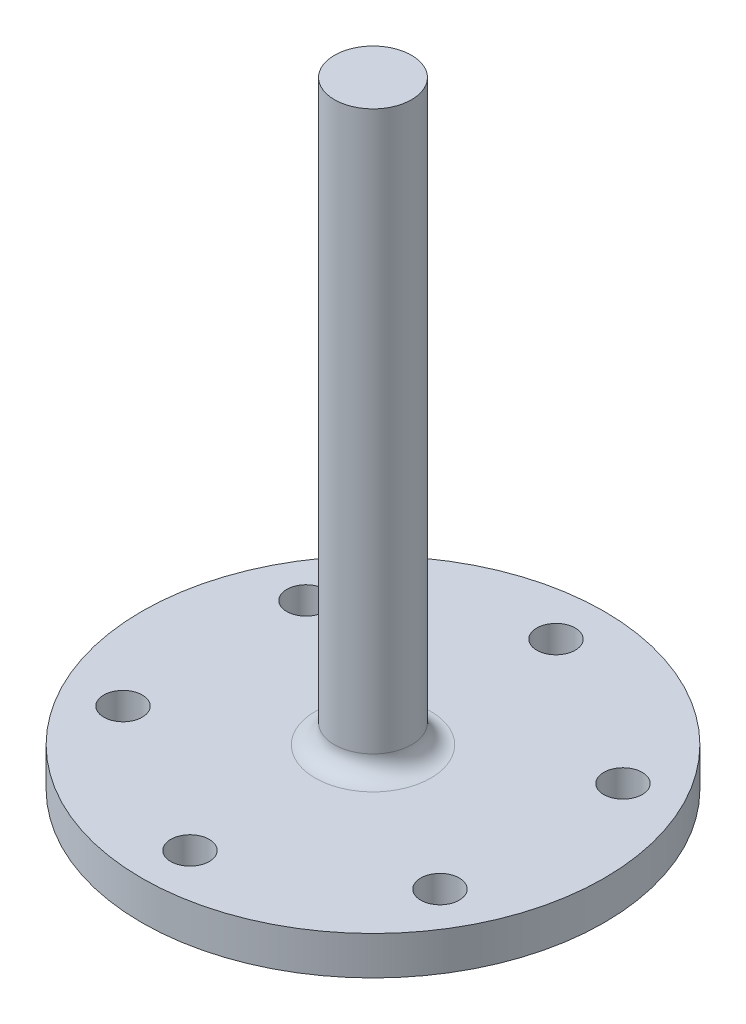
SolidWorks part; units mm, degrees
ref_plane "Front Plane" through (0, 0, 0) normal (0, 0, 1) x (1, 0, 0)
ref_plane "Top Plane" through (0, 0, 0) normal (0, 1, 0) x (1, 0, 0)
ref_plane "Right Plane" through (0, 0, 0) normal (1, 0, 0) x (0, 0, -1)
sketch "Sketch1" plane through (0, 0, 0) normal (0, 1, 0) x (1, 0, 0)
  line L0 (0, 0) -> (-20.5681, 11.875) construction
  line L1 (0, 0) -> (0, 23.75)
  line L2 (0, 0) -> (20.5681, 11.875) construction
  line L3 (0, 0) -> (-20.5681, -11.875) construction
  line L4 (0, 0) -> (0, -23.75) construction
  line L5 (0, 0) -> (20.5681, -11.875) construction
  circle A0 centre (0, 0) radius 30
  circle A2 centre (-20.5681, 11.875) radius 2.5
  circle A3 centre (0, 23.75) radius 2.5
  circle A4 centre (20.5681, 11.875) radius 2.5
  circle A5 centre (20.5681, -11.875) radius 2.5
  circle A6 centre (0, -23.75) radius 2.5
  circle A7 centre (-20.5681, -11.875) radius 2.5
extrude "Boss-Extrude1" add sketch "Sketch1" along normal blind 5 contours A5 | A4 | A3 | A2 | A7 | A6 | A0
sketch "Sketch2" plane through (0, 5, 0) normal (0, 1, 0) x (1, 0, 0)
  circle A0 centre (0, 0) radius 5
extrude "Boss-Extrude2" add sketch "Sketch2" along normal blind 75
fillet "Fillet1" radius 2.5 1 edges at (0, 5, 5)
